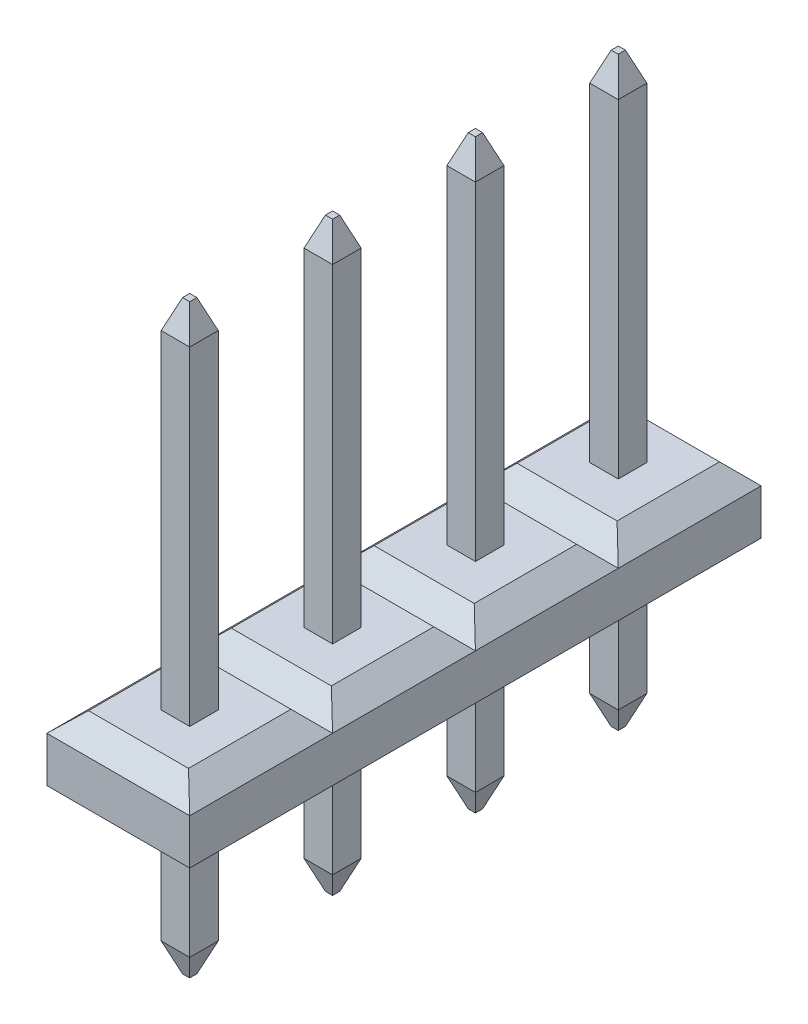
SolidWorks part; units mm, degrees
ref_plane "Front Plane" through (0, 0, 0) normal (0, 0, 1) x (1, 0, 0)
ref_plane "Top Plane" through (0, 0, 0) normal (0, 1, 0) x (1, 0, 0)
ref_plane "Right Plane" through (0, 0, 0) normal (1, 0, 0) x (0, 0, -1)
sketch "Sketch1" plane through (0, 0, 0) normal (0, 1, 0) x (1, 0, 0)
  line L1 (0, 0) -> (2.54, 0)
  line L2 (0, 0) -> (0, 2.54)
  line L3 (0, 2.54) -> (2.54, 2.54)
  line L4 (2.54, 0) -> (2.54, 2.54)
  dimension "D1" = 2.54
  dimension "D2" = 2.54
extrude "Boss-Extrude1" add sketch "Sketch1" along normal blind 1.524
sketch "Sketch2" plane through (0, 1.524, 0) normal (0, 1, 0) x (1, 0, 0)
  line L0 (0, 2.54) -> (0, 0) construction
  line L1 (0, 0) -> (2.54, 0) construction
  line L2 (1.27, 0) -> (1.27, 2.0363) construction
  line L3 (1.524, 1.524) -> (1.016, 1.524)
  line L4 (1.524, 1.524) -> (1.524, 1.016)
  line L5 (1.524, 1.016) -> (1.016, 1.016)
  line L6 (1.016, 1.524) -> (1.016, 1.016)
  line L7 (1.524, 1.524) -> (1.016, 1.016) construction
  line L8 (1.524, 1.016) -> (1.016, 1.524) construction
  line L9 (0, 1.27) -> (2.1183, 1.27) construction
  point P0 (0, 1.27)
  point P1 (1.27, 0)
  point P4 (1.27, 1.27)
  point P7 (1.27, 1.27)
  dimension "D1" = 0.508
  dimension "D2" = 0.508
  dimension "D3" = 0
  dimension "D4" = 0
extrude "Boss-Extrude2" add sketch "Sketch2" along normal blind 6.35
sketch "Sketch3" plane through (0, 0, 0) normal (0, -1, 0) x (1, 0, 0)
  line L4 (1.016, -1.016) -> (1.016, -1.524)
  line L5 (1.524, -1.016) -> (1.016, -1.016)
  line L6 (1.524, -1.524) -> (1.524, -1.016)
  line L7 (1.016, -1.524) -> (1.524, -1.524)
  line L8 (1.016, -1.016) -> (1.016, -1.524)
  line L9 (1.524, -1.016) -> (1.016, -1.016)
  line L10 (1.524, -1.524) -> (1.524, -1.016)
  line L11 (1.016, -1.524) -> (1.524, -1.524)
  dimension "D1" = 0
extrude "Boss-Extrude3" add sketch "Sketch3" along normal blind 2.54
chamfer "Chamfer1" distance 0.508 distance2 0.1905 4 edges at (1.524, 7.874, -1.27) (1.27, 7.874, -1.524) (1.016, 7.874, -1.27) (1.27, 7.874, -1.016)
chamfer "Chamfer2" distance 0.508 distance2 0.1905 4 edges at (1.524, -2.54, -1.27) (1.27, -2.54, -1.524) (1.016, -2.54, -1.27) (1.27, -2.54, -1.016)
sketch "Sketch4" plane through (0, 0, -2.54) normal (0, 0, -1) x (-1, 0, 0)
  line L0 (-2.54, 1.1645) -> (-2.159, 1.524)
  line L1 (-2.54, 1.524) -> (-2.54, 0) construction
  line L2 (-2.54, 1.524) -> (0, 1.524) construction
  line L3 (-2.159, 1.524) -> (-2.54, 1.524)
  line L4 (-2.54, 1.524) -> (-2.54, 1.1645)
  line L5 (-1.27, 1.524) -> (-1.27, 0) construction
  line L6 (-2.54, 0) -> (0, 0) construction
  line L7 (-2.54, 0.762) -> (0, 0.762) construction
  line L8 (0, 1.524) -> (0, 0) construction
  line L9 (0, 1.524) -> (0, 1.1645)
  line L10 (-0.381, 1.524) -> (0, 1.524)
  line L11 (0, 1.1645) -> (-0.381, 1.524)
  line L12 (0, 0.3595) -> (-0.381, 0)
  line L13 (-0.381, 0) -> (0, 0)
  line L14 (0, 0) -> (0, 0.3595)
  line L15 (-2.54, 0) -> (-2.54, 0.3595)
  line L16 (-2.159, 0) -> (-2.54, 0)
  line L17 (-2.54, 0.3595) -> (-2.159, 0)
  dimension "D1" = 0.381
extrude "Cut-Extrude1" cut sketch "Sketch4" against normal blind 2.54
sketch "Sketch5" plane through (0, 0, 0) normal (-1, 0, 0) x (0, 0, 1)
  line L0 (-2.54, 1.1645) -> (-2.159, 1.5455)
  line L1 (-2.159, 1.5455) -> (-2.54, 1.5455)
  line L2 (-2.54, 1.5455) -> (-2.54, 1.1645)
  line L3 (0, 1.1645) -> (-2.54, 1.1645) construction
  line L4 (-2.54, 0.762) -> (0, 0.762) construction
  line L5 (-2.54, 1.1645) -> (-2.54, 0.3595) construction
  line L6 (0, 1.1645) -> (0, 0.3595) construction
  line L7 (-1.27, 0.762) -> (-1.27, 1.5455) construction
  line L8 (0, 1.5455) -> (0, 1.1645)
  line L9 (-0.381, 1.5455) -> (0, 1.5455)
  line L10 (0, 1.1645) -> (-0.381, 1.5455)
  line L11 (-2.54, -0.0215) -> (-2.54, 0.3595)
  line L12 (-2.159, -0.0215) -> (-2.54, -0.0215)
  line L13 (-2.54, 0.3595) -> (-2.159, -0.0215)
  line L14 (0, 0.3595) -> (-0.381, -0.0215)
  line L15 (-0.381, -0.0215) -> (0, -0.0215)
  line L16 (0, -0.0215) -> (0, 0.3595)
  dimension "D1" = 0.381
  dimension "D2" = 0.381
  dimension "D3" = 0.381
extrude "Cut-Extrude2" cut sketch "Sketch5" against normal blind 2.54
pattern_linear "LPattern5" count 4 spacing 2.54 along (0, 0, 1) of "Boss-Extrude1", "Boss-Extrude2", "Chamfer1", "Chamfer2", "Boss-Extrude3", "Cut-Extrude1", "Cut-Extrude2"
